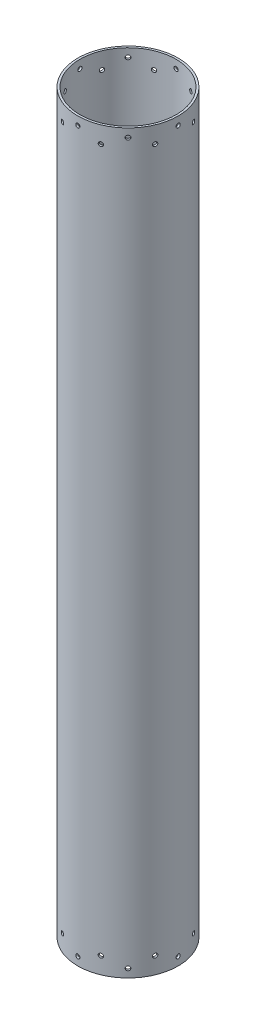
SolidWorks part; units mm, degrees
material "6061-T6 (SS)"
ref_plane "Front Plane" through (0, 0, 0) normal (0, 0, 1) x (1, 0, 0)
ref_plane "Top Plane" through (0, 0, 0) normal (0, 1, 0) x (1, 0, 0)
ref_plane "Right Plane" through (0, 0, 0) normal (1, 0, 0) x (0, 0, -1)
sketch "Sketch2" plane through (0, 0, 0) normal (0, 1, 0) x (1, 0, 0)
  circle A0 centre (0, 0) radius 76.2
  circle A1 centre (0, 0) radius 73.025
  dimension "D1" = 152.4
  dimension "D2" = 3.175
extrude "Boss-Extrude1" add sketch "Sketch2" along normal blind 1117.6
sketch "Sketch3" plane through (0, 0, 0) normal (0, 0, 1) x (1, 0, 0)
  line L0 (0, 1117.6) -> (0, 1104.9) construction
  line L1 (73.025, 1117.6) -> (-73.025, 1117.6) construction
  circle A0 centre (0, 1104.9) radius 3.175
  dimension "D1" = 6.35
  dimension "D2" = 12.7
extrude "Cut-Extrude1" cut sketch "Sketch3" against normal blind 1143
pattern_circular "CirPattern1" count 8 over 360 about axis through (0, 1117.6, 0) along (0, -1, 0) of "Cut-Extrude1"
ref_plane "Plane1" through (-29.1605, 0, 70.3996) normal (-0.3827, 0, 0.9239) x (0, -1, 0)
sketch "Sketch6" plane through (-29.1605, 0, 70.3996) normal (-0.3827, 0, 0.9239) x (0, -1, 0)
  line L0 (-1117.6, 0) -> (-1092.2, 0) construction
  line L1 (-1117.6, 76.2) -> (-1117.6, -76.2) construction
  circle A0 centre (-1092.2, 0) radius 3.175
  dimension "D1" = 6.35
  dimension "D2" = 25.4
extrude "Cut-Extrude2" cut sketch "Sketch6" against normal blind 25.4
pattern_circular "CirPattern2" count 8 over 360 about axis through (0, 1117.6, 0) along (0, -1, 0) of "Cut-Extrude2"
ref_plane "Plane2" through (0, 558.8, 0) normal (0, 1, 0) x (1, 0, 0)
mirror "Mirror1" about plane through (0, 558.8, 0) normal (0, 1, 0) of "CirPattern2", "CirPattern1", "Cut-Extrude1", "Cut-Extrude2"
